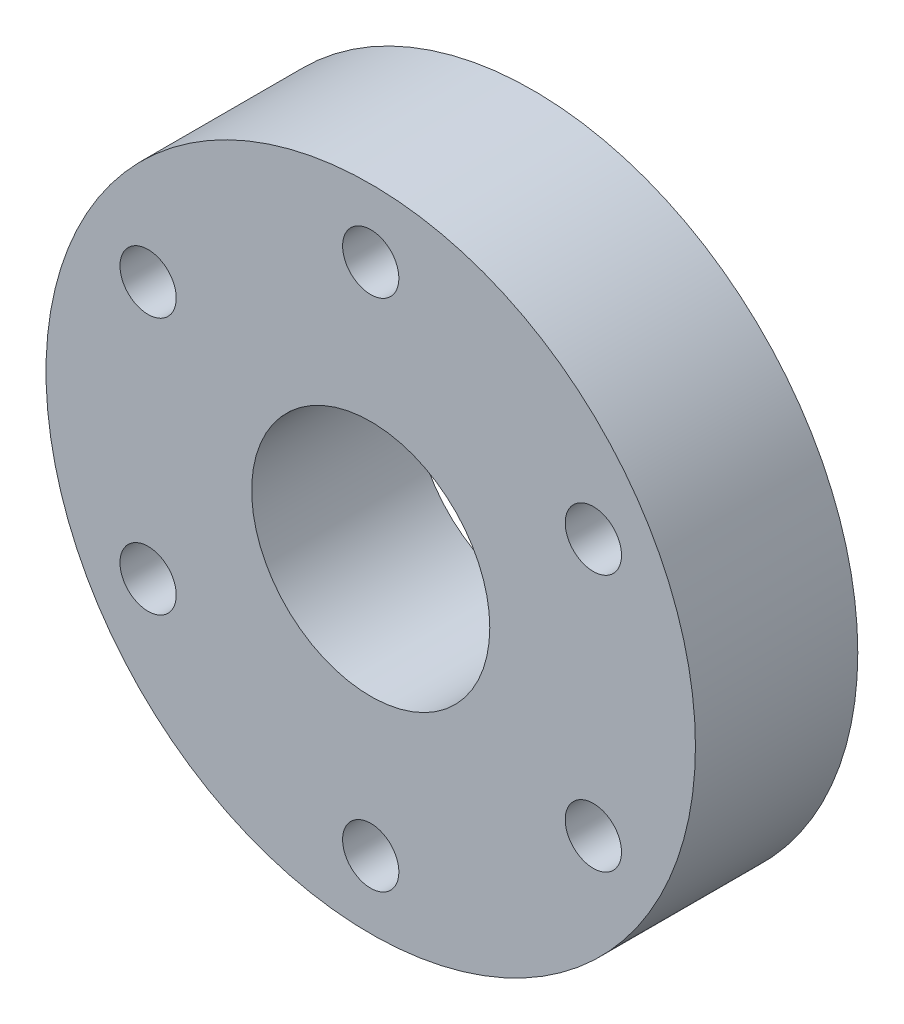
SolidWorks part; units mm, degrees
ref_plane "Front Plane" through (0, 0, 0) normal (0, 0, 1) x (1, 0, 0)
ref_plane "Top Plane" through (0, 0, 0) normal (0, 1, 0) x (1, 0, 0)
ref_plane "Right Plane" through (0, 0, 0) normal (1, 0, 0) x (0, 0, -1)
sketch "Sketch1" plane through (0, 0, 0) normal (0, 0, 1) x (1, 0, 0)
  circle A0 centre (0, 0) radius 30
  circle A1 centre (0, 23.75) radius 2.6
  circle A2 centre (20.5681, 11.875) radius 2.6
  circle A3 centre (20.5681, -11.875) radius 2.6
  circle A4 centre (0, -23.75) radius 2.6
  circle A5 centre (-20.5681, -11.875) radius 2.6
  circle A6 centre (-20.5681, 11.875) radius 2.6
  circle A7 centre (0, 0) radius 11
  point P17 (0, 0)
  dimension "D1" = 60
  dimension "D2" = 5.2
  dimension "D5" = 22
  dimension "D3" = 23.75
  dimension "D4" = 6
extrude "Boss-Extrude1" add sketch "Sketch1" along normal blind 15
